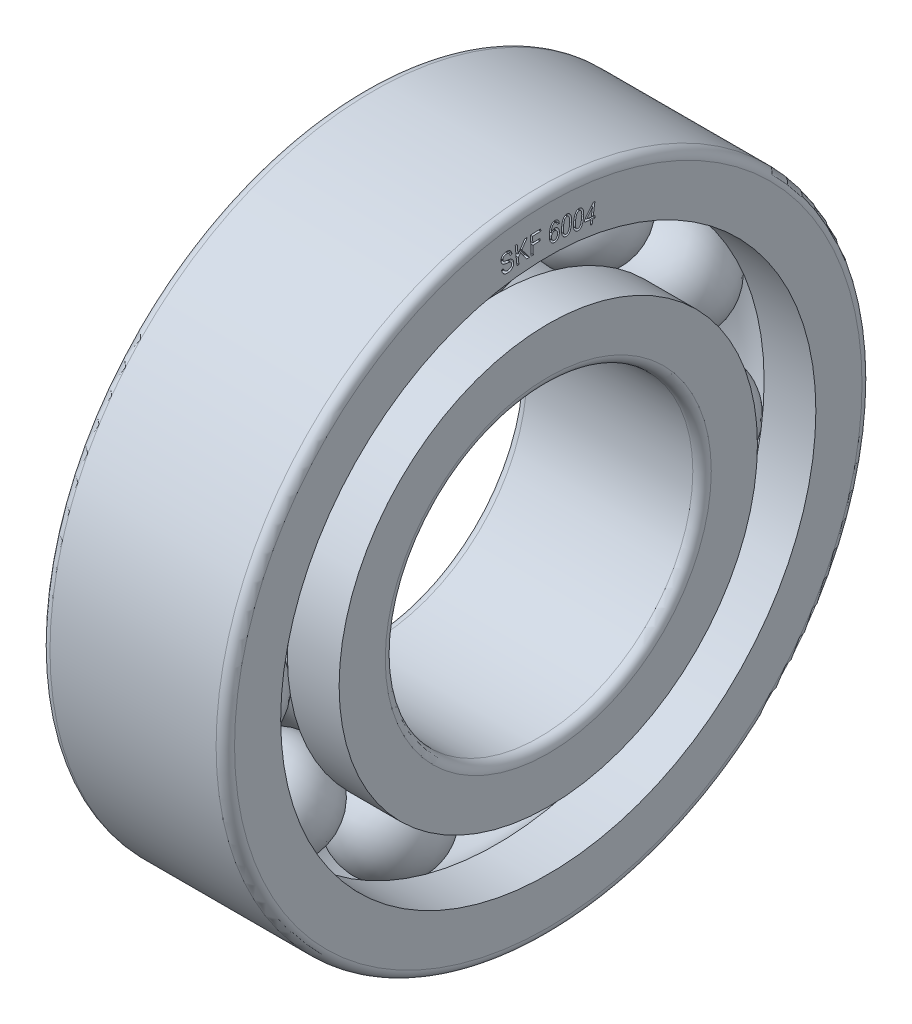
SolidWorks part; units mm, degrees
ref_plane "Alzado" through (0, 0, 0) normal (0, 0, 1) x (1, 0, 0)
ref_plane "Planta" through (0, 0, 0) normal (0, 1, 0) x (1, 0, 0)
ref_plane "Vista lateral" through (0, 0, 0) normal (1, 0, 0) x (0, 0, -1)
sketch "Sketch1" plane through (0, 0, 0) normal (0, 0, 1) x (1, 0, 0)
  line L0 (0, 0) -> (29.9021, 0) construction
  line L1 (0, 17.4) -> (3.3632, 17.4)
  line L2 (0, 21) -> (12, 21)
  line L3 (0, 21) -> (0, 17.4)
  line L4 (0, 10) -> (12, 10)
  line L5 (12, 21) -> (12, 17.4)
  line L6 (0, 13.6) -> (3.3632, 13.6)
  line L7 (0, 13.6) -> (0, 10)
  line L8 (12, 13.6) -> (12, 10)
  line L9 (0, 17.4) -> (0, 13.6) construction
  line L10 (0, 15.5) -> (12, 15.5) construction
  line L11 (8.6368, 13.6) -> (12, 13.6)
  line L12 (8.6368, 17.4) -> (12, 17.4)
  arc A0 (3.3632, 13.6) -> (8.6368, 13.6) centre (6, 15.5) ccw
  arc A1 (8.6368, 17.4) -> (3.3632, 17.4) centre (6, 15.5) ccw
  dimension "D6" = 6.5
  dimension "D1" = 12
  dimension "D2" = 10
  dimension "D3" = 21
  dimension "D4" = 17.4
  dimension "D5" = 13.6
revolve "Revolve1" add sketch "Sketch1" angle 360 about L0
fillet "Fillet1" radius 0.6 2 edges at (0, 0, 21) (12, 0, 21)
fillet "Fillet2" radius 0.6 2 edges at (0, 0, 10) (12, 0, 10)
sketch "Sketch2" plane through (0, 0, 0) normal (0, 0, 1) x (1, 0, 0)
  line L0 (6, 18.75) -> (6, 12.25)
  arc A0 (6, 18.75) -> (6, 12.25) centre (6, 15.5) ccw
  arc A1 (8.6368, 17.4) -> (3.3632, 17.4) centre (6, 15.5) ccw construction
revolve "Revolve2" add sketch "Sketch2" angle 360 about L0
pattern_circular "CirPattern2" count 11 over 360 about axis through (0, 0, 0) along (1, 0, 0) of bodies 103
sketch "Sketch4" plane through (12, 0, 0) normal (1, 0, 0) x (0, 0, -1)
  arc A0 (-6.131, 16.9237) -> (6.131, 16.9237) centre (0, 0) cw construction
  circle A1 centre (0, 0) radius 17.4 construction
  text T0 "SKF 6004\r\n" font "Arial Narrow" height 1.2
  dimension "D1" = 0.6
extrude "Cut-Extrude1" cut sketch "Sketch4" against normal blind 0.3
